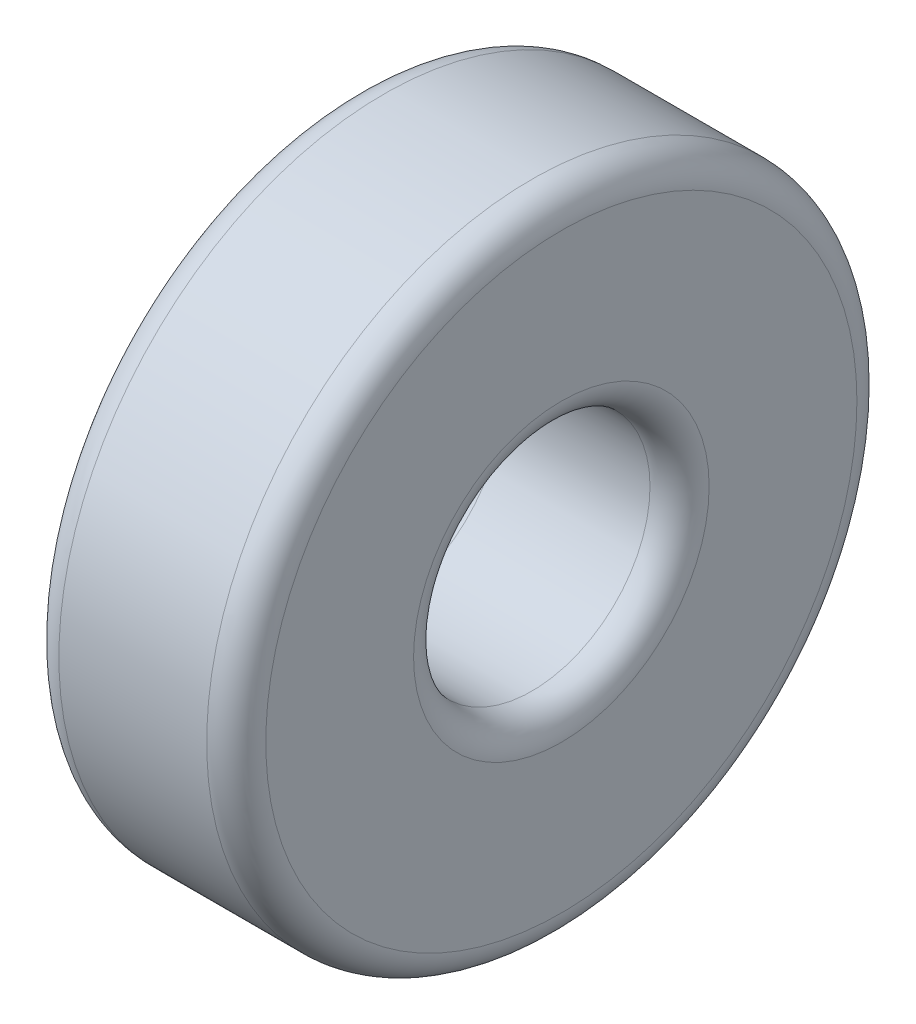
SolidWorks part; units mm, degrees
ref_plane "前视基准面" through (0, 0, 0) normal (0, 0, 1) x (1, 0, 0)
ref_plane "上视基准面" through (0, 0, 0) normal (0, 1, 0) x (1, 0, 0)
ref_plane "右视基准面" through (0, 0, 0) normal (1, 0, 0) x (0, 0, -1)
sketch "草图1" plane through (0, 0, 0) normal (1, 0, 0) x (0, 0, -1)
  circle A0 centre (0, 0) radius 11
  circle A1 centre (0, 0) radius 4
  dimension "D1" = 8
  dimension "D2" = 22
extrude "凸台-拉伸1" add sketch "草图1" along normal blind 7
fillet "圆角1" radius 1 4 edges at (0, 0, -4) (7, 0, -4) (0, 0, -11) (7, 0, -11)
